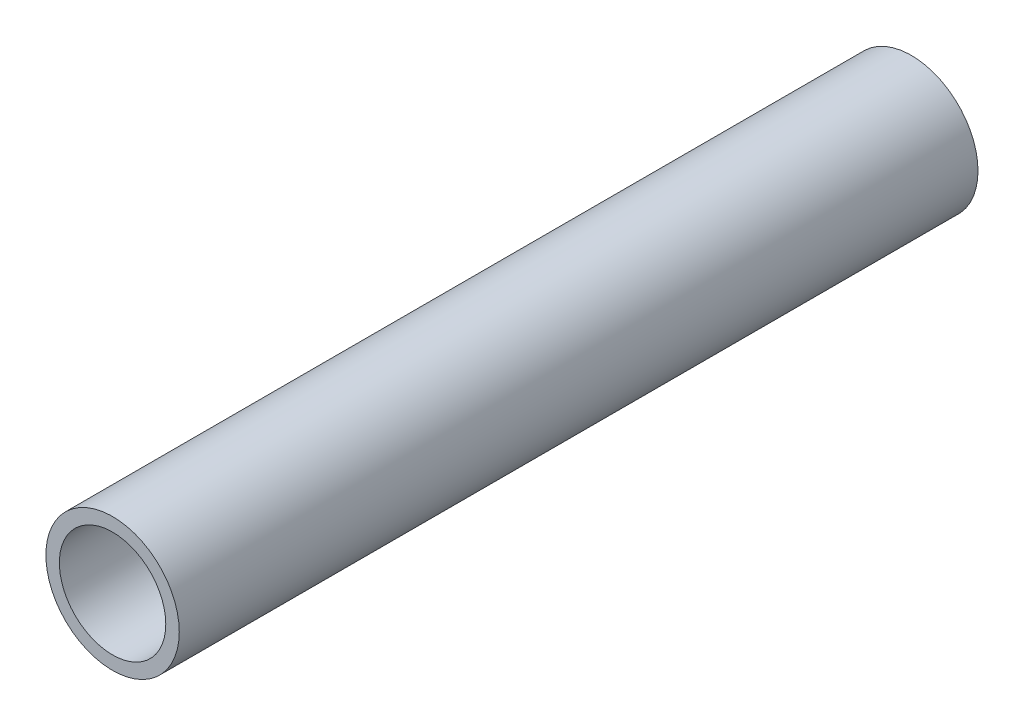
SolidWorks part; units mm, degrees
ref_plane "Front Plane" through (0, 0, 0) normal (0, 0, 1) x (1, 0, 0)
ref_plane "Top Plane" through (0, 0, 0) normal (0, 1, 0) x (1, 0, 0)
ref_plane "Right Plane" through (0, 0, 0) normal (1, 0, 0) x (0, 0, -1)
sketch "Sketch1" plane through (0, 0, 0) normal (0, 0, 1) x (1, 0, 0)
  circle A0 centre (0, 0) radius 16.7005
  dimension "Pipe OD" = 33.401
extrude "Extrude-Thin1" add sketch "Sketch1" along normal mid plane 200 thin thin type one direction reverse wall 3.3782
